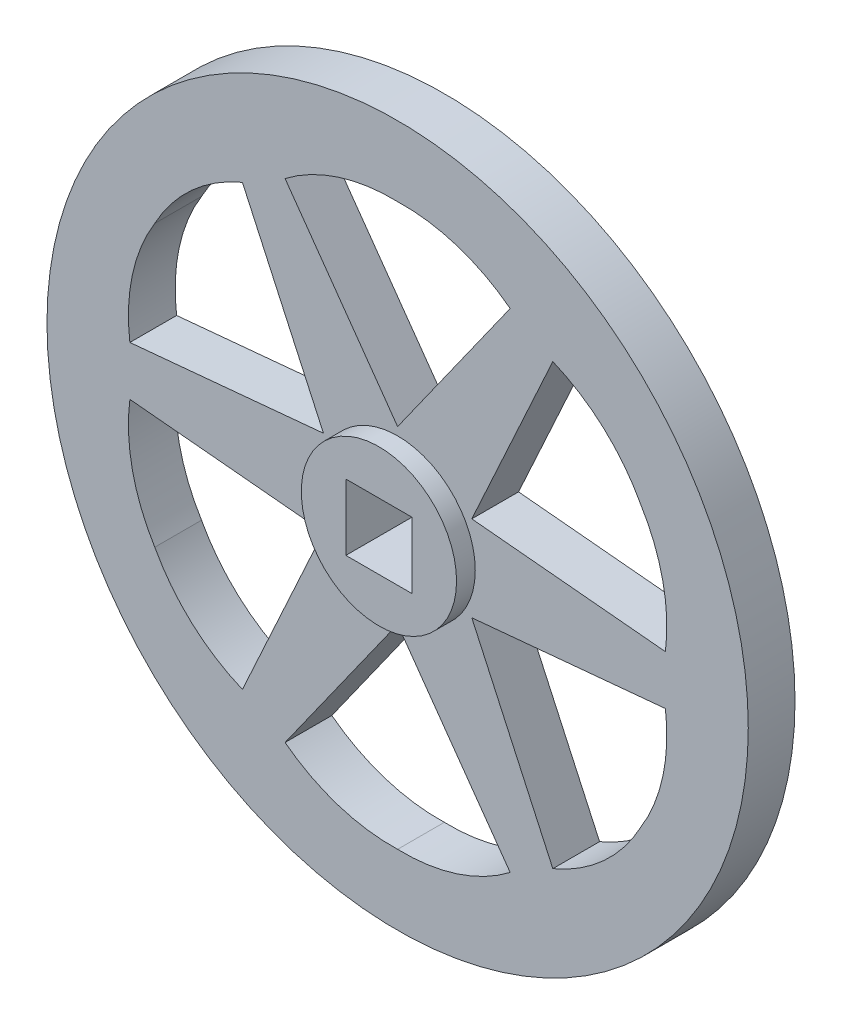
SolidWorks part; units mm, degrees
ref_plane "Front Plane" through (0, 0, 0) normal (0, 0, 1) x (1, 0, 0)
ref_plane "Top Plane" through (0, 0, 0) normal (0, 1, 0) x (1, 0, 0)
ref_plane "Right Plane" through (0, 0, 0) normal (1, 0, 0) x (0, 0, -1)
sketch "Sketch1" plane through (0, 0, 0) normal (0, 0, 1) x (1, 0, 0)
  line L1 (3.5355, -3.5355) -> (-3.5355, -3.5355)
  line L2 (3.5355, -3.5355) -> (3.5355, 3.5355)
  line L3 (3.5355, 3.5355) -> (-3.5355, 3.5355)
  line L4 (-3.5355, -3.5355) -> (-3.5355, 3.5355)
  line L5 (3.5355, -3.5355) -> (-3.5355, 3.5355) construction
  line L6 (3.5355, 3.5355) -> (-3.5355, -3.5355) construction
  circle A0 centre (0, 0) radius 37.5
  circle A1 centre (0, 0) radius 5 construction
  dimension "D1" = 75
  dimension "D2" = 10
extrude "Boss-Extrude1" add sketch "Sketch1" along normal mid plane 5
sketch "Sketch2" plane through (0, 0, 0) normal (0, 0, 1) x (1, 0, 0)
  line L0 (0, 0) -> (0, 32.5712) construction
  line L1 (0, 9.1586) -> (-12.0371, 26.1152)
  line L2 (0, 9.1586) -> (12.0371, 26.1152)
  arc A0 (-12.0371, 26.1152) -> (0, 29.9881) centre (-0.5568, 11.0765) cw
  arc A1 (12.0371, 26.1152) -> (0, 29.9881) centre (0.5568, 11.0765) ccw
extrude "Cut-Extrude1" cut sketch "Sketch2" along normal mid plane 8
pattern_circular "CirPattern1" count 6 over 360 about axis through (0, 0, 0) along (0, 0, 1) of "Cut-Extrude1"
sketch "Sketch4" plane through (0, 0, 2.5) normal (0, 0, 1) x (1, 0, 0)
  line L1 (3.5355, -3.5355) -> (-3.5355, -3.5355)
  line L2 (3.5355, -3.5355) -> (3.5355, 3.5355)
  line L3 (3.5355, 3.5355) -> (-3.5355, 3.5355)
  line L4 (-3.5355, -3.5355) -> (-3.5355, 3.5355)
  line L5 (3.5355, -3.5355) -> (-3.5355, 3.5355) construction
  line L6 (3.5355, 3.5355) -> (-3.5355, -3.5355) construction
  circle A0 centre (0, 0) radius 8.3027
  circle A1 centre (0, 0) radius 5 construction
extrude "Boss-Extrude2" add sketch "Sketch4" along normal blind 2
